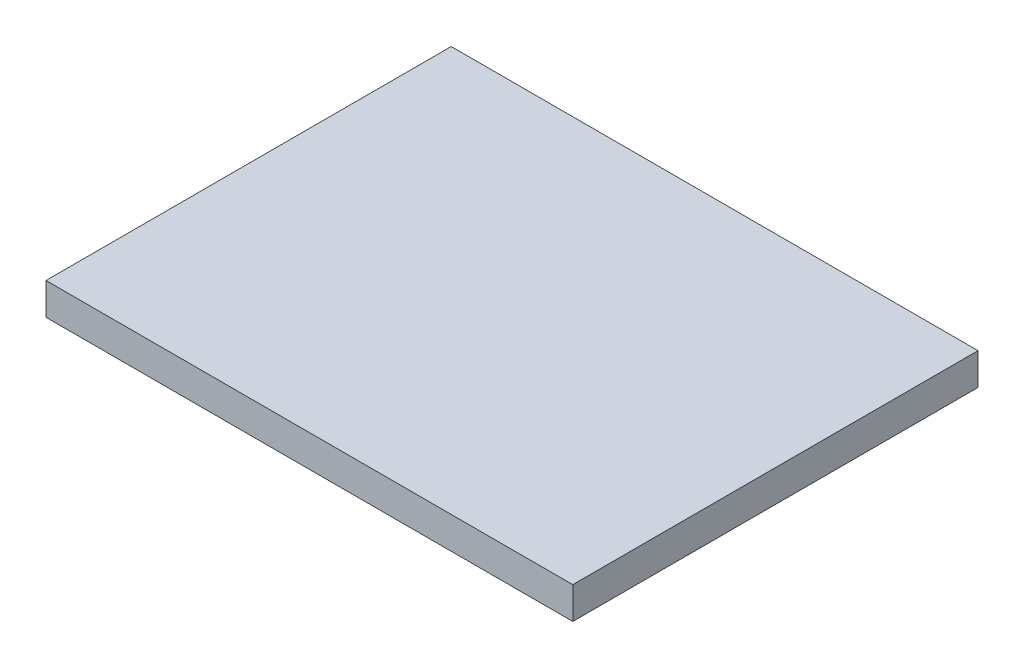
SolidWorks part; units mm, degrees
ref_plane "Front Plane" through (0, 0, 0) normal (0, 0, 1) x (1, 0, 0)
ref_plane "Top Plane" through (0, 0, 0) normal (0, 1, 0) x (1, 0, 0)
ref_plane "Right Plane" through (0, 0, 0) normal (1, 0, 0) x (0, 0, -1)
sketch "Sketch1" plane through (0, 0, 0) normal (0, 1, 0) x (1, 0, 0)
  line L1 (-104.164, 64.8021) -> (60.936, 64.8021)
  line L2 (-104.164, 64.8021) -> (-104.164, -62.1979)
  line L3 (-104.164, -62.1979) -> (60.936, -62.1979)
  line L4 (60.936, 64.8021) -> (60.936, -62.1979)
  dimension "D1" = 127
  dimension "D2" = 165.1
extrude "Boss-Extrude1" add sketch "Sketch1" along normal blind 10
